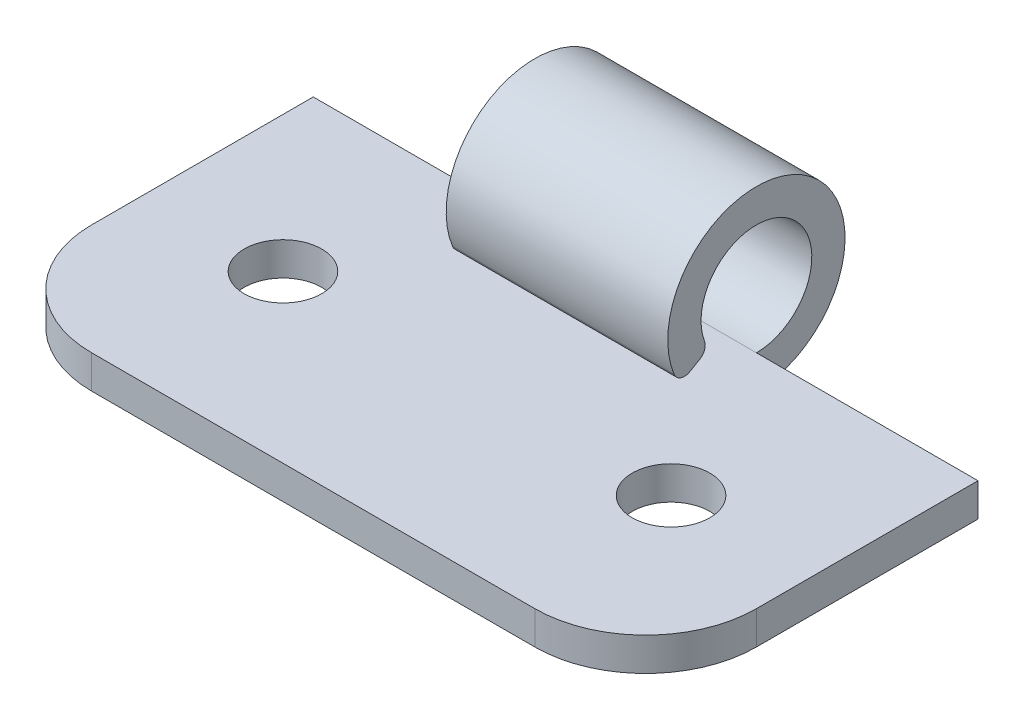
SolidWorks part; units mm, degrees
ref_plane "前视基准面" through (0, 0, 0) normal (0, 0, 1) x (1, 0, 0)
ref_plane "上视基准面" through (0, 0, 0) normal (0, 1, 0) x (1, 0, 0)
ref_plane "右视基准面" through (0, 0, 0) normal (1, 0, 0) x (0, 0, -1)
other "Configuration Table"
sketch "草图1" plane through (0, 0, 0) normal (0, 1, 0) x (1, 0, 0)
  line L0 (-15, -7.5) -> (15, -7.5)
  line L1 (-15, -7.5) -> (-15, 7.5)
  line L2 (-15, 7.5) -> (15, 7.5)
  line L3 (15, -7.5) -> (15, 7.5)
  line L4 (-15, -7.5) -> (15, 7.5) construction
  line L5 (-15, 7.5) -> (15, -7.5) construction
  circle A0 centre (-8.8673, 0) radius 1.75
  circle A1 centre (8.6474, 0) radius 1.75
  point P0 (0, 0)
  dimension "D3" = 3.5
  dimension "D5" = 3.5
  dimension "D1" = 30
  dimension "D2" = 15
  dimension "D4" = 7.5
  dimension "D6" = 7.5
extrude "凸台-拉伸1" add sketch "草图1" along normal blind 1.5
fillet "圆角1" radius 5 2 edges at (15, 0.75, 7.5) (-15, 0.75, 7.5)
sketch "草图2" plane through (0, 0, 0) normal (1, 0, 0) x (0, 0, -1)
  line L0 (7.5, 0) -> (7.5, 4) construction
  line L4 (4.9383, 2.521) -> (4.5, 2.2679)
  line L5 (7.5, 1.5) -> (7.5, 0)
  arc A5 (7.5, 0) -> (3.7857, 2.5154) centre (7.5, 4) ccw
  arc A6 (7.5, 1.5) -> (5.1569, 3.1283) centre (7.5, 4) ccw
  arc A7 (4.5, 2.2679) -> (3.7857, 2.5154) centre (4.25, 2.701) cw
  arc A8 (5.1569, 3.1283) -> (4.9383, 2.521) centre (4.6883, 2.954) cw
  dimension "D1" = 0.5
  dimension "D2" = 5
  dimension "D3" = 60
extrude "凸台-拉伸3" add sketch "草图2" along normal mid plane 10
